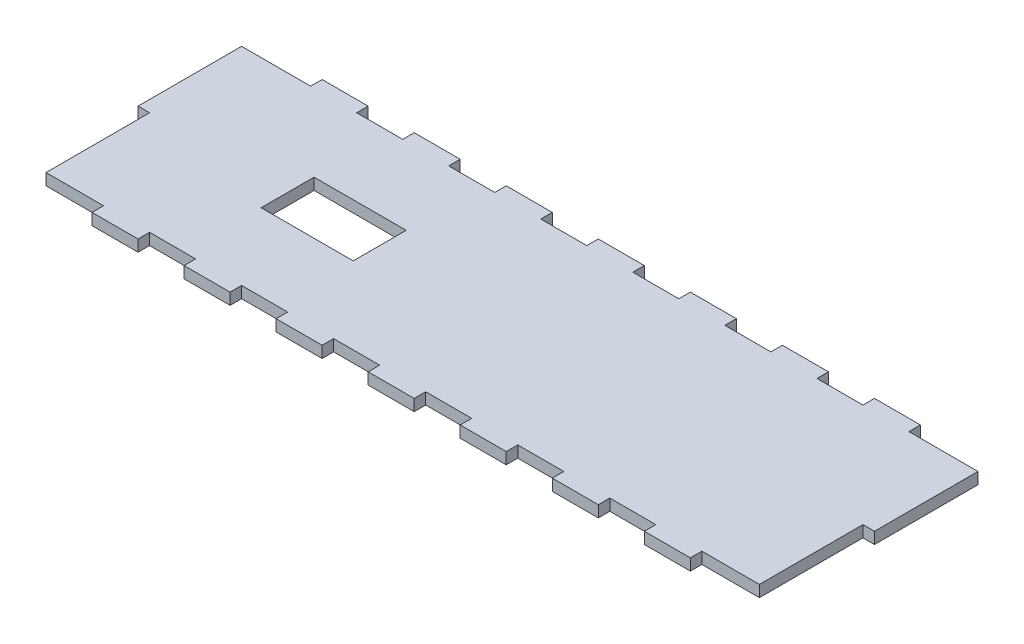
SolidWorks part; units mm, degrees
material "Oak"
ref_plane "Front Plane" through (0, 0, 0) normal (0, 0, 1) x (1, 0, 0)
ref_plane "Top Plane" through (0, 0, 0) normal (0, 1, 0) x (1, 0, 0)
ref_plane "Right Plane" through (0, 0, 0) normal (1, 0, 0) x (0, 0, -1)
sketch "Sketch1" plane through (0, 0, 0) normal (0, 1, 0) x (1, 0, 0)
  line L1 (80, 25) -> (-80, 25)
  line L2 (80, 25) -> (80, -25)
  line L3 (80, -25) -> (-80, -25)
  line L4 (-80, 25) -> (-80, -25)
  line L5 (80, 25) -> (-80, -25) construction
  line L6 (80, -25) -> (-80, 25) construction
  point P0 (0, 0)
  dimension "D1" = 50
  dimension "D2" = 160
extrude "Boss-Extrude1" add sketch "Sketch1" along normal mid plane 2.5
sketch "Sketch2" plane through (0, 1.25, 0) normal (0, 1, 0) x (1, 0, 0)
  line L0 (5, -22.5) -> (-5, -22.5) construction
  line L5 (80, 25) -> (-80, 25) construction
  line L6 (5, 25) -> (-5, 25) construction
  line L11 (5, -22.5) -> (5, -25) construction
  line L24 (5, -25) -> (-5, -25) construction
  line L85 (5, 25) -> (5, 22.5) construction
  line L86 (5, 22.5) -> (-5, 22.5) construction
  line L87 (-5, 25) -> (-5, 22.5) construction
  line L88 (80, -25) -> (80, 25) construction
  line L89 (-5, -22.5) -> (-5, -25) construction
  line L90 (-80, -25) -> (80, -25) construction
  line L115 (25, 22.5) -> (25, 25)
  line L140 (5, 22.5) -> (15, 22.5)
  line L141 (5, 22.5) -> (5, 25)
  line L142 (5, 25) -> (15, 25)
  line L143 (15, 22.5) -> (15, 25)
  line L144 (5, -22.5) -> (15, -22.5)
  line L145 (5, -22.5) -> (5, -25)
  line L146 (5, -25) -> (15, -25)
  line L147 (15, -22.5) -> (15, -25)
  line L148 (25, 22.5) -> (35, 22.5)
  line L149 (35, 22.5) -> (35, 25)
  line L150 (25, 25) -> (35, 25)
  line L151 (25, -22.5) -> (25, -25)
  line L152 (25, -22.5) -> (35, -22.5)
  line L153 (35, -22.5) -> (35, -25)
  line L154 (25, -25) -> (35, -25)
  line L155 (45, 22.5) -> (45, 25)
  line L156 (45, 22.5) -> (55, 22.5)
  line L157 (55, 22.5) -> (55, 25)
  line L158 (45, 25) -> (55, 25)
  line L159 (45, -22.5) -> (45, -25)
  line L160 (45, -22.5) -> (55, -22.5)
  line L161 (55, -22.5) -> (55, -25)
  line L162 (45, -25) -> (55, -25)
  line L163 (5, 22.5) -> (25, 22.5) construction
  line L164 (-15, 22.5) -> (-15, 25)
  line L165 (-15, 22.5) -> (-5, 22.5)
  line L166 (-5, 22.5) -> (-5, 25)
  line L167 (-15, 25) -> (-5, 25)
  line L168 (-15, -22.5) -> (-15, -25)
  line L169 (-15, -22.5) -> (-5, -22.5)
  line L170 (-5, -22.5) -> (-5, -25)
  line L171 (-15, -25) -> (-5, -25)
  line L172 (-35, 22.5) -> (-35, 25)
  line L173 (-35, 22.5) -> (-25, 22.5)
  line L174 (-25, 22.5) -> (-25, 25)
  line L175 (-35, 25) -> (-25, 25)
  line L176 (-35, -22.5) -> (-35, -25)
  line L177 (-35, -22.5) -> (-25, -22.5)
  line L178 (-25, -22.5) -> (-25, -25)
  line L179 (-35, -25) -> (-25, -25)
  line L180 (-55, 22.5) -> (-55, 25)
  line L181 (-55, 22.5) -> (-45, 22.5)
  line L182 (-45, 22.5) -> (-45, 25)
  line L183 (-55, 25) -> (-45, 25)
  line L184 (-55, -22.5) -> (-55, -25)
  line L185 (-55, -22.5) -> (-45, -22.5)
  line L186 (-45, -22.5) -> (-45, -25)
  line L187 (-55, -25) -> (-45, -25)
  line L188 (5, 22.5) -> (-15, 22.5) construction
  line L190 (80, 25) -> (65, 25)
  line L191 (80, 25) -> (80, 22.5)
  line L192 (80, 22.5) -> (65, 22.5)
  line L193 (65, 25) -> (65, 22.5)
  line L194 (80, -25) -> (65, -25)
  line L195 (80, -25) -> (80, -22.5)
  line L196 (80, -22.5) -> (65, -22.5)
  line L197 (65, -25) -> (65, -22.5)
  line L198 (-80, 25) -> (-65, 25)
  line L199 (-80, 25) -> (-80, 22.5)
  line L200 (-80, 22.5) -> (-65, 22.5)
  line L201 (-65, 25) -> (-65, 22.5)
  line L202 (-80, -25) -> (-65, -25)
  line L203 (-80, -25) -> (-80, -22.5)
  line L204 (-80, -22.5) -> (-65, -22.5)
  line L205 (-65, -25) -> (-65, -22.5)
  dimension "D2" = 2.5
  dimension "D1" = 10
  dimension "D3" = 75
  dimension "D4" = 10
  dimension "D5" = 2.5
  dimension "D6" = 75
  dimension "D7" = 10
  dimension "D8" = 10
  dimension "D10" = 20
  dimension "D12" = 20
  dimension "D13" = 2.5
  dimension "D14" = 2.5
  dimension "D15" = 2.5
  dimension "D16" = 2.5
  dimension "D17" = 10
  dimension "D18" = 10
  dimension "D19" = 10
  dimension "D20" = 10
  dimension "D9" = 3
  dimension "D11" = 4
extrude "Cut-Extrude1" cut sketch "Sketch2" against normal blind 4
sketch "Sketch3" plane through (0, 1.25, 0) normal (0, 1, 0) x (1, 0, 0)
  line L0 (0, 0) -> (0, 25) construction
  line L1 (80, 0) -> (77.5, 0)
  line L2 (80, 0) -> (80, -22.5)
  line L3 (80, -22.5) -> (77.5, -22.5)
  line L4 (77.5, 0) -> (77.5, -22.5)
  line L5 (80, -22.5) -> (80, 22.5) construction
  line L6 (5, 25) -> (-5, 25) construction
  line L14 (80, -22.5) -> (65, -22.5) construction
  line L15 (-77.5, 0) -> (-77.5, -22.5)
  line L16 (-80, -22.5) -> (-77.5, -22.5)
  line L17 (-80, 0) -> (-80, -22.5)
  line L18 (-80, 0) -> (-77.5, 0)
  point P5 (78.75, -22.5)
  dimension "D2" = 2.5
  dimension "D3" = 22.5
extrude "Cut-Extrude2" cut sketch "Sketch3" against normal through all
sketch "Sketch4" plane through (0, -1.25, 0) normal (0, -1, 0) x (-1, 0, 0)
  line L1 (47.5, 5.75) -> (27.5, 5.75)
  line L2 (47.5, 5.75) -> (47.5, -5.75)
  line L3 (47.5, -5.75) -> (27.5, -5.75)
  line L4 (27.5, 5.75) -> (27.5, -5.75)
  line L5 (77.5, -22.5) -> (77.5, 0) construction
  point P6 (27.5, 0)
  dimension "D1" = 20
  dimension "D2" = 30
  dimension "D3" = 11.5
extrude "Cut-Extrude3" cut sketch "Sketch4" against normal up to next
equation "\"thick\"= 0.25"
equation "\"D2@Sketch3\"=\"thick\""
equation "\"corner\"=2.1"
equation "\"D3@Sketch3\"=( +\"width\" - \"thick\" * 2 ) / 2"
equation "\"D1@Boss-Extrude1\"=\"thick\""
equation "\"length\"= 16"
equation "\"width\"=5"
equation "\"D1@Sketch1\"=\"width\""
equation "\"D2@Sketch1\"=\"length\""
equation "\"hole_length\"=1"
equation "\"D1@Sketch2\"=\"hole_length\""
equation "\"D6@Sketch2\"=\"D3@Sketch2\""
equation "\"D5@Sketch2\"=\"thick\""
equation "\"D4@Sketch2\"=\"hole_length\""
equation "\"D3@Sketch2\"=(\"length\" - 1) / 2"
equation "\"D2@Sketch2\"=\"thick\""
equation "\"D7@Sketch2\"=\"D1@Sketch2\""
equation "\"D8@Sketch2\"=\"D1@Sketch2\""
equation "\"D13@Sketch2\"=\"thick\""
equation "\"D14@Sketch2\"=\"D13@Sketch2\""
equation "\"D15@Sketch2\"=\"D13@Sketch2\""
equation "\"D16@Sketch2\"=\"D15@Sketch2\""
equation "\"D17@Sketch2\"=\"hole_length\""
equation "\"D18@Sketch2\"=\"D17@Sketch2\""
equation "\"D19@Sketch2\"=\"D18@Sketch2\""
equation "\"D20@Sketch2\"=\"D19@Sketch2\""
